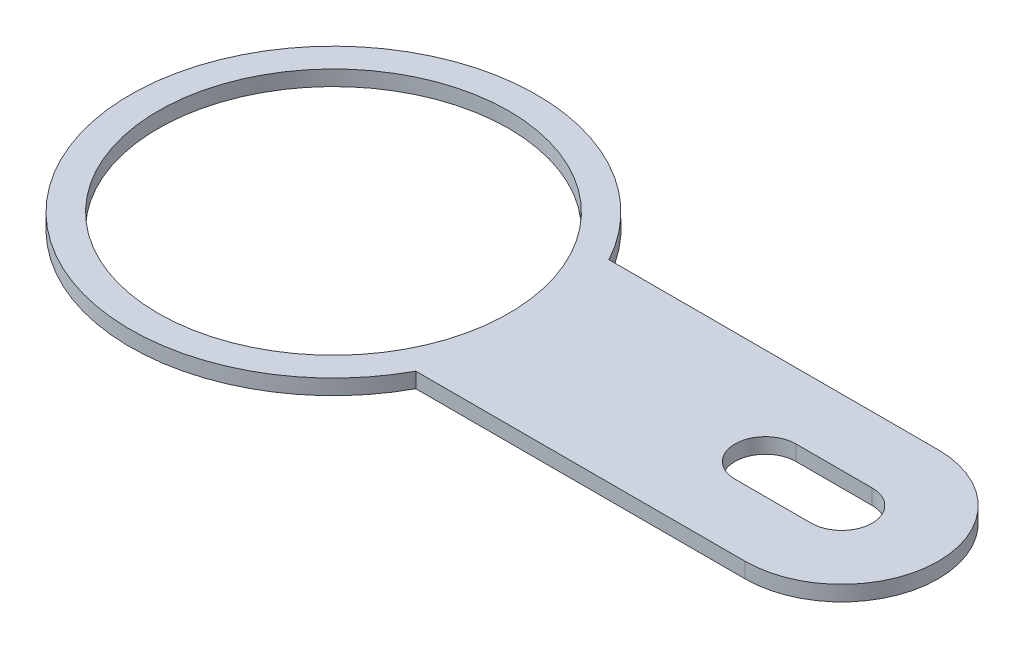
SolidWorks part; units mm, degrees
ref_plane "前视基准面" through (0, 0, 0) normal (0, 0, 1) x (1, 0, 0)
ref_plane "上视基准面" through (0, 0, 0) normal (0, 1, 0) x (1, 0, 0)
ref_plane "右视基准面" through (0, 0, 0) normal (1, 0, 0) x (0, 0, -1)
sketch "草图1" plane through (0, 0, 0) normal (0, 1, 0) x (1, 0, 0)
  line L0 (-77.6751, 0) -> (79.1379, 0) construction
  line L1 (0, 39.057) -> (0, -47.8338) construction
  line L2 (3.5199, 1.9) -> (10, 1.9)
  line L3 (3.5199, -1.9) -> (10, -1.9)
  line L4 (10, 12.8834) -> (10, -14.4726) construction
  line L5 (10, 0) -> (8.5, 0) construction
  line L6 (10, -0.6) -> (8.5, -0.6)
  line L7 (10, 0.6) -> (8.5, 0.6)
  circle A0 centre (0, 0) radius 3.45
  arc A1 (10, 1.9) -> (10, -1.9) centre (10, 0) cw
  arc A2 (10, -0.6) -> (10, 0.6) centre (10, 0) ccw
  arc A3 (8.5, 0.6) -> (8.5, -0.6) centre (8.5, 0) ccw
  arc A4 (3.5199, -1.9) -> (3.5199, 1.9) centre (0, 0) cw
  point P14 (9.25, 0)
  dimension "D1" = 6.9
  dimension "D2" = 1.9
  dimension "D5" = 4
  dimension "D3" = 1.2
  dimension "D4" = 10
  dimension "D6" = 1.5
extrude "凸台-拉伸1" add sketch "草图1" along normal blind 0.3
